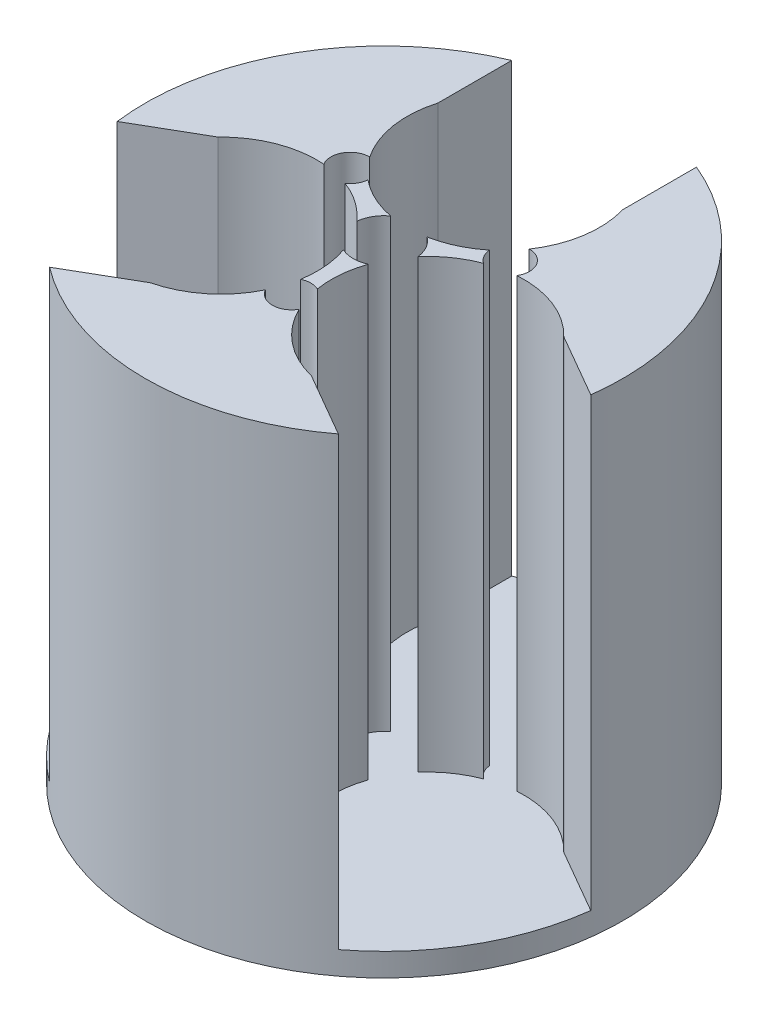
SolidWorks part; units mm, degrees
ref_plane "Front Plane" through (0, 0, 0) normal (0, 0, 1) x (1, 0, 0)
ref_plane "Top Plane" through (0, 0, 0) normal (0, 1, 0) x (1, 0, 0)
ref_plane "Right Plane" through (0, 0, 0) normal (1, 0, 0) x (0, 0, -1)
sketch "Sketch1" plane through (0, 0, 0) normal (0, 1, 0) x (1, 0, 0)
  circle A0 centre (0, 0) radius 31
  dimension "D1" = 62
extrude "Boss-Extrude1" add sketch "Sketch1" along normal blind 50
sketch "Sketch2" plane through (0, 50, 0) normal (0, 1, 0) x (1, 0, 0)
  circle A0 centre (0, 0) radius 22.5 construction
  circle A1 centre (0, 15.5) radius 7 construction
  circle A2 centre (0, 15.5) radius 12.5
  circle A3 centre (13.4234, -7.75) radius 12.5
  circle A4 centre (-13.4234, -7.75) radius 12.5
  dimension "D1" = 45
  dimension "D2" = 15.5
  dimension "D3" = 14
  dimension "D4" = 25
  dimension "D5" = 3
extrude "Cut-Extrude1" cut sketch "Sketch2" against normal blind 50
sketch "Sketch3" plane through (0, 50, 0) normal (0, 1, 0) x (1, 0, 0)
  line L0 (0, 0) -> (0, 31) construction
  line L1 (0, 0) -> (26.8468, -15.5) construction
  line L2 (0, 0) -> (-26.8468, -15.5) construction
  line L4 (12, 12) -> (12, 32.5)
  line L6 (-4.3923, -16.3923) -> (-22.1458, -26.6423)
  line L7 (4.3923, -16.3923) -> (22.1458, -26.6423)
  line L8 (16.3923, 4.3923) -> (34.1458, -5.8577)
  line L9 (-12, 12) -> (-12, 32.5)
  line L10 (-16.3923, 4.3923) -> (-34.1458, -5.8577)
  circle A0 centre (13.4234, -7.75) radius 12.5 construction
  circle A1 centre (-13.4234, -7.75) radius 12.5 construction
  circle A2 centre (0, 15.5) radius 12.5 construction
  circle A3 centre (13.4234, -7.75) radius 12.5
  circle A4 centre (-13.4234, -7.75) radius 12.5
  circle A5 centre (0, 15.5) radius 12.5
  circle A6 centre (0, 0) radius 31 construction
  circle A7 centre (0, 0) radius 31
  circle M9 centre (-13.4234, -7.75) radius 12.5
  circle M10 centre (13.4234, -7.75) radius 12.5
  circle M11 centre (0, 15.5) radius 12.5
  circle M12 centre (0, 0) radius 31
  dimension "D2" = 25
  dimension "D3" = 25
  dimension "D4" = 12
  dimension "D1" = 3
extrude "Cut-Extrude2" cut sketch "Sketch3" against normal blind 50 contours L10 L6 M9 M12 | L10 L6 M9 | L9 L4 M11 | L9 L4 M11 M12 | L8 L7 M10 | L8 L7 M10 M12 | A7
sketch "Sketch4" plane through (0, 50, 0) normal (0, 1, 0) x (1, 0, 0)
  line L0 (0, 0) -> (0, -31) construction
  line L1 (0, 0) -> (-26.8468, 15.5) construction
  line L2 (0, 0) -> (26.8468, 15.5) construction
  circle A0 centre (0, 0) radius 4
  arc A5 (-18.7538, -24.6839) -> (18.7538, -24.6839) centre (0, 0) ccw construction
  circle A6 centre (-10.3923, 6) radius 2.5
  circle A7 centre (10.3923, 6) radius 2.5
  circle A8 centre (0, -12) radius 2.5
  dimension "D1" = 8
  dimension "D5" = 3
  dimension "D3" = 5
  dimension "D4" = 12
  dimension "D2" = 3
extrude "Cut-Extrude3" cut sketch "Sketch4" against normal through all
sketch "Sketch6" plane through (0, 0, 0) normal (0, -1, 0) x (1, 0, 0)
  circle A0 centre (0, 0) radius 31
extrude "Boss-Extrude2" add sketch "Sketch6" along normal blind 3
sketch "Sketch7" plane through (0, 50, 0) normal (0, 1, 0) x (1, 0, 0)
  line L0 (-10.4545, -19.8923) -> (-18.7538, -24.6839) construction
  line L1 (18.7538, -24.6839) -> (10.4545, -19.8923) construction
  line L2 (22.4545, 0.8923) -> (30.7538, -3.8993) construction
  line L3 (12, 28.5832) -> (12, 19) construction
  line L4 (-12, 19) -> (-12, 28.5832) construction
  line L5 (-30.7538, -3.8993) -> (-22.4545, 0.8923) construction
  line L6 (-10.4545, -19.8923) -> (-18.7538, -24.6839)
  line L7 (18.7538, -24.6839) -> (10.4545, -19.8923)
  line L8 (22.4545, 0.8923) -> (30.7538, -3.8993)
  line L9 (12, 28.5832) -> (12, 19)
  line L10 (-12, 19) -> (-12, 28.5832)
  line L11 (-30.7538, -3.8993) -> (-22.4545, 0.8923)
  arc A0 (-2.183, -13.2184) -> (2.183, -13.2184) centre (0, -12) ccw construction
  arc A1 (-10.4545, -19.8923) -> (-2.183, -13.2184) centre (-13.4234, -7.75) ccw construction
  arc A2 (-18.7538, -24.6839) -> (18.7538, -24.6839) centre (0, 0) ccw construction
  arc A3 (2.183, -13.2184) -> (10.4545, -19.8923) centre (13.4234, -7.75) ccw construction
  arc A4 (1.084, -9.7472) -> (-1.084, -9.7472) centre (0, -12) ccw construction
  arc A5 (1.611, -3.6612) -> (1.084, -9.7472) centre (13.4234, -7.75) ccw construction
  arc A6 (-1.611, -3.6612) -> (1.611, -3.6612) centre (0, 0) ccw construction
  arc A7 (-1.084, -9.7472) -> (-1.611, -3.6612) centre (-13.4234, -7.75) ccw construction
  arc A8 (12.539, 4.7187) -> (10.356, 8.4997) centre (10.3923, 6) ccw construction
  arc A9 (22.4545, 0.8923) -> (12.539, 4.7187) centre (13.4234, -7.75) ccw construction
  arc A10 (30.7538, -3.8993) -> (12, 28.5832) centre (0, 0) ccw construction
  arc A11 (10.356, 8.4997) -> (12, 19) centre (0, 15.5) ccw construction
  arc A12 (7.8994, 5.8124) -> (8.9833, 3.9349) centre (10.3923, 6) ccw construction
  arc A13 (2.3652, 3.2258) -> (7.8994, 5.8124) centre (0, 15.5) ccw construction
  arc A14 (3.9762, 0.4354) -> (2.3652, 3.2258) centre (0, 0) ccw construction
  arc A15 (8.9833, 3.9349) -> (3.9762, 0.4354) centre (13.4234, -7.75) ccw construction
  arc A16 (-8.9833, 3.9349) -> (-7.8994, 5.8124) centre (-10.3923, 6) ccw construction
  arc A17 (-3.9762, 0.4354) -> (-8.9833, 3.9349) centre (-13.4234, -7.75) ccw construction
  arc A18 (-2.3652, 3.2258) -> (-3.9762, 0.4354) centre (0, 0) ccw construction
  arc A19 (-7.8994, 5.8124) -> (-2.3652, 3.2258) centre (0, 15.5) ccw construction
  arc A20 (-10.356, 8.4997) -> (-12.539, 4.7187) centre (-10.3923, 6) ccw construction
  arc A21 (-12, 19) -> (-10.356, 8.4997) centre (0, 15.5) ccw construction
  arc A22 (-12, 28.5832) -> (-30.7538, -3.8993) centre (0, 0) ccw construction
  arc A23 (-12.539, 4.7187) -> (-22.4545, 0.8923) centre (-13.4234, -7.75) ccw construction
  arc A24 (-2.183, -13.2184) -> (2.183, -13.2184) centre (0, -12) ccw
  arc A25 (-10.4545, -19.8923) -> (-2.183, -13.2184) centre (-13.4234, -7.75) ccw
  arc A26 (-18.7538, -24.6839) -> (18.7538, -24.6839) centre (0, 0) ccw
  arc A27 (2.183, -13.2184) -> (10.4545, -19.8923) centre (13.4234, -7.75) ccw
  arc A28 (1.084, -9.7472) -> (-1.084, -9.7472) centre (0, -12) ccw
  arc A29 (1.611, -3.6612) -> (1.084, -9.7472) centre (13.4234, -7.75) ccw
  arc A30 (-1.611, -3.6612) -> (1.611, -3.6612) centre (0, 0) ccw
  arc A31 (-1.084, -9.7472) -> (-1.611, -3.6612) centre (-13.4234, -7.75) ccw
  arc A32 (12.539, 4.7187) -> (10.356, 8.4997) centre (10.3923, 6) ccw
  arc A33 (22.4545, 0.8923) -> (12.539, 4.7187) centre (13.4234, -7.75) ccw
  arc A34 (30.7538, -3.8993) -> (12, 28.5832) centre (0, 0) ccw
  arc A35 (10.356, 8.4997) -> (12, 19) centre (0, 15.5) ccw
  arc A36 (7.8994, 5.8124) -> (8.9833, 3.9349) centre (10.3923, 6) ccw
  arc A37 (2.3652, 3.2258) -> (7.8994, 5.8124) centre (0, 15.5) ccw
  arc A38 (3.9762, 0.4354) -> (2.3652, 3.2258) centre (0, 0) ccw
  arc A39 (8.9833, 3.9349) -> (3.9762, 0.4354) centre (13.4234, -7.75) ccw
  arc A40 (-8.9833, 3.9349) -> (-7.8994, 5.8124) centre (-10.3923, 6) ccw
  arc A41 (-3.9762, 0.4354) -> (-8.9833, 3.9349) centre (-13.4234, -7.75) ccw
  arc A42 (-2.3652, 3.2258) -> (-3.9762, 0.4354) centre (0, 0) ccw
  arc A43 (-7.8994, 5.8124) -> (-2.3652, 3.2258) centre (0, 15.5) ccw
  arc A44 (-10.356, 8.4997) -> (-12.539, 4.7187) centre (-10.3923, 6) ccw
  arc A45 (-12, 19) -> (-10.356, 8.4997) centre (0, 15.5) ccw
  arc A46 (-12, 28.5832) -> (-30.7538, -3.8993) centre (0, 0) ccw
  arc A47 (-12.539, 4.7187) -> (-22.4545, 0.8923) centre (-13.4234, -7.75) ccw
extrude "Boss-Extrude3" add sketch "Sketch7" along normal blind 8
